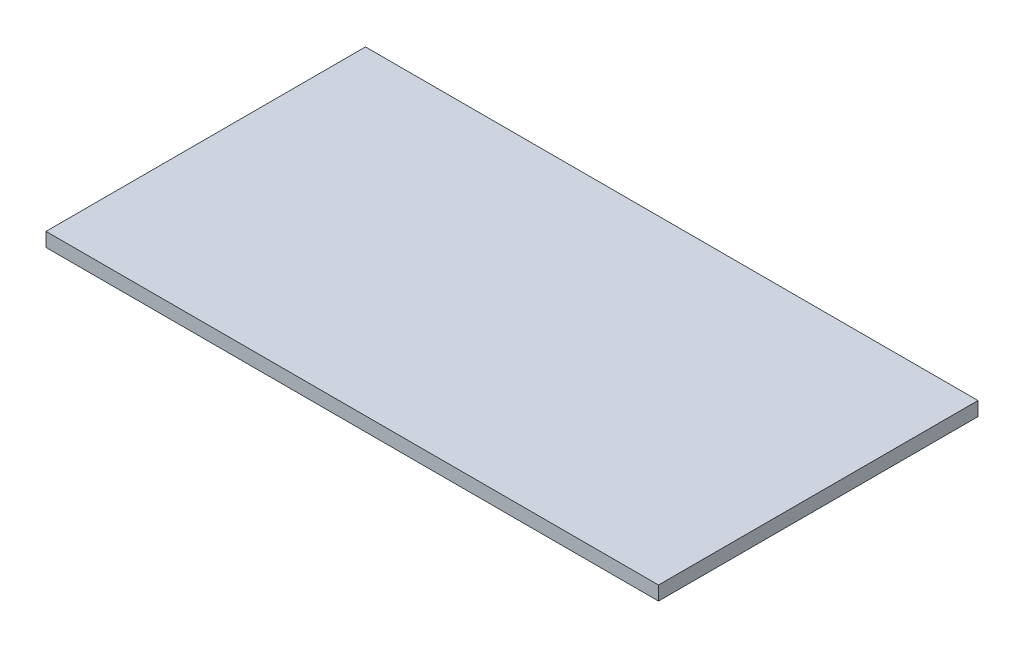
SolidWorks part; units mm, degrees
ref_plane "Front" through (0, 0, 0) normal (0, 0, 1) x (1, 0, 0)
ref_plane "Top" through (0, 0, 0) normal (0, 1, 0) x (1, 0, 0)
ref_plane "Right" through (0, 0, 0) normal (1, 0, 0) x (0, 0, -1)
sketch "Sketch1" plane through (0, 0, 0) normal (0, 1, 0) x (1, 0, 0)
  line L1 (55.7447, -29.0767) -> (-55.7447, -29.0767)
  line L2 (55.7447, -29.0767) -> (55.7447, 29.0767)
  line L3 (55.7447, 29.0767) -> (-55.7447, 29.0767)
  line L4 (-55.7447, -29.0767) -> (-55.7447, 29.0767)
  line L5 (55.7447, -29.0767) -> (-55.7447, 29.0767) construction
  line L6 (55.7447, 29.0767) -> (-55.7447, -29.0767) construction
  point P0 (0, 0)
extrude "Boss-Extrude1" add sketch "Sketch1" along normal blind 2.54
